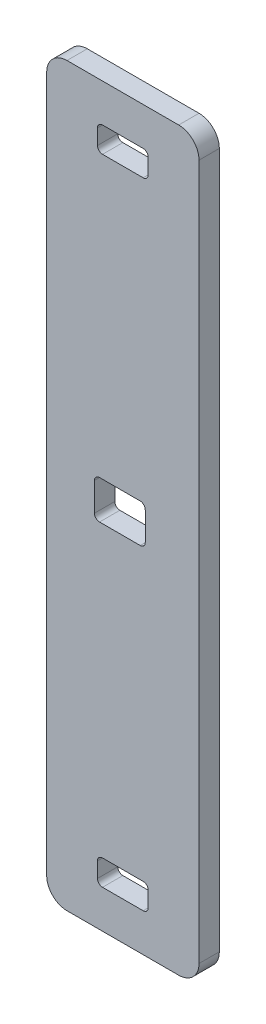
SolidWorks part; units mm, degrees
ref_plane "Plan de face" through (0, 0, 0) normal (0, 0, 1) x (1, 0, 0)
ref_plane "Plan de dessus" through (0, 0, 0) normal (0, 1, 0) x (1, 0, 0)
ref_plane "Plan de droite" through (0, 0, 0) normal (1, 0, 0) x (0, 0, -1)
sketch "Esquisse1" plane through (0, 0, 0) normal (0, 0, 1) x (1, 0, 0)
  line L1 (-11, -72.5) -> (11, -72.5)
  line L2 (-15, -68.5) -> (-15, 68.5)
  line L3 (-11, 72.5) -> (11, 72.5)
  line L4 (15, -68.5) -> (15, 68.5)
  line L5 (-15, -72.5) -> (15, 72.5) construction
  line L6 (-15, 72.5) -> (15, -72.5) construction
  arc A0 (-11, -72.5) -> (-15, -68.5) centre (-11, -68.5) cw
  arc A1 (11, -72.5) -> (15, -68.5) centre (11, -68.5) ccw
  arc A2 (-15, 68.5) -> (-11, 72.5) centre (-11, 68.5) cw
  arc A3 (11, 72.5) -> (15, 68.5) centre (11, 68.5) cw
  point P0 (0, 0)
  dimension "D3" = 4
  dimension "D1" = 145
  dimension "D2" = 30
extrude "Boss.-Extru.1" add sketch "Esquisse1" along normal blind 4
sketch "Esquisse2" plane through (0, 0, 4) normal (0, 0, 1) x (1, 0, 0)
  line L0 (11, 72.5) -> (-11, 72.5) construction
  line L1 (-4, -60) -> (4, -60)
  line L2 (-5, -61) -> (-5, -64)
  line L3 (-4, -65) -> (4, -65)
  line L4 (5, -61) -> (5, -64)
  line L5 (-5, -60) -> (5, -65) construction
  line L6 (-5, -65) -> (5, -60) construction
  line L7 (-4, 65) -> (4, 65)
  line L8 (-5, 64) -> (-5, 61)
  line L9 (-4, 60) -> (4, 60)
  line L10 (5, 64) -> (5, 61)
  line L11 (-5, 65) -> (5, 60) construction
  line L12 (-5, 60) -> (5, 65) construction
  line L13 (-11, -72.5) -> (11, -72.5) construction
  line L14 (-4.5876, 4.585) -> (3.4124, 4.585)
  line L15 (-15, 68.5) -> (-15, -68.5) construction
  line L16 (-5.5876, 3.585) -> (-5.5876, -2)
  line L17 (-4.5876, -3) -> (3.4124, -3)
  line L18 (4.4124, 3.585) -> (4.4124, -2)
  line L19 (-5.5876, 4.585) -> (4.4124, -3) construction
  line L20 (-5.5876, -3) -> (4.4124, 4.585) construction
  line L22 (-11, -72.5) -> (11, -72.5) construction
  arc A0 (-4, 65) -> (-5, 64) centre (-4, 64) ccw
  arc A1 (-5, 61) -> (-4, 60) centre (-4, 61) ccw
  arc A2 (4, 60) -> (5, 61) centre (4, 61) ccw
  arc A3 (4, 65) -> (5, 64) centre (4, 64) cw
  arc A4 (-4, -60) -> (-5, -61) centre (-4, -61) ccw
  arc A5 (-5, -64) -> (-4, -65) centre (-4, -64) ccw
  arc A6 (4, -65) -> (5, -64) centre (4, -64) ccw
  arc A7 (4, -60) -> (5, -61) centre (4, -61) cw
  arc A8 (-4.5876, 4.585) -> (-5.5876, 3.585) centre (-4.5876, 3.585) ccw
  arc A9 (-5.5876, -2) -> (-4.5876, -3) centre (-4.5876, -2) ccw
  arc A10 (3.4124, -3) -> (4.4124, -2) centre (3.4124, -2) ccw
  arc A11 (3.4124, 4.585) -> (4.4124, 3.585) centre (3.4124, 3.585) cw
  point P0 (0, -62.5)
  point P5 (0, 62.5)
  point P41 (-0.5876, 0.7925)
  dimension "D9" = 1
  dimension "D10" = 1
  dimension "D11" = 1
  dimension "D1" = 7.5
  dimension "D2" = 7.5
  dimension "D3" = 5
  dimension "D4" = 5
  dimension "D5" = 10
  dimension "D6" = 15
  dimension "D7" = 10
  dimension "D8" = 15
  dimension "D12" = 69.5
extrude "Enlèv. mat.-Extru.1" cut sketch "Esquisse2" against normal through all
